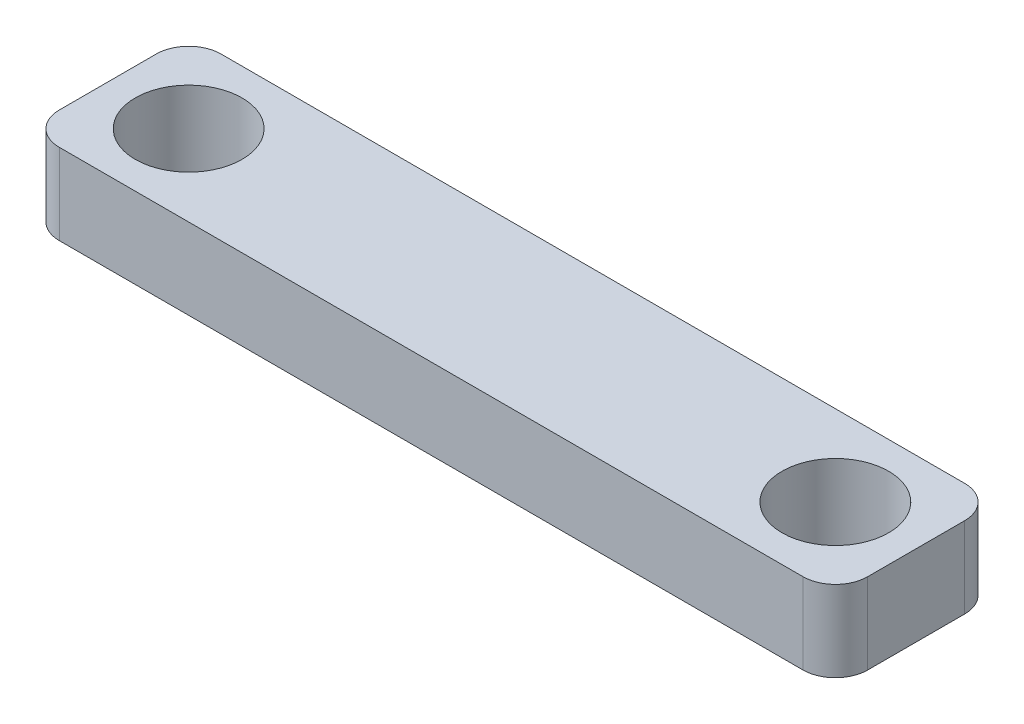
SolidWorks part; units mm, degrees
ref_plane "前视基准面" through (0, 0, 0) normal (0, 0, 1) x (1, 0, 0)
ref_plane "上视基准面" through (0, 0, 0) normal (0, 1, 0) x (1, 0, 0)
ref_plane "右视基准面" through (0, 0, 0) normal (1, 0, 0) x (0, 0, -1)
sketch "草图1" plane through (0, 0, 0) normal (0, 1, 0) x (1, 0, 0)
  line L1 (0, 0) -> (250, 0)
  line L2 (0, 0) -> (0, 50)
  line L3 (0, 50) -> (250, 50)
  line L4 (250, 0) -> (250, 50)
  circle A0 centre (25, 25) radius 16.5
  circle A1 centre (225, 25) radius 16.5
  dimension "D3" = 33
  dimension "D4" = 33
  dimension "D1" = 250
  dimension "D2" = 50
  dimension "D5" = 25
  dimension "D6" = 25
  dimension "D7" = 25
  dimension "D8" = 25
extrude "凸台-拉伸1" add sketch "草图1" along normal blind 25
fillet "圆角1" radius 10 4 edges at (0, 12.5, -50) (0, 12.5, 0) (250, 12.5, -50) (250, 12.5, 0)
